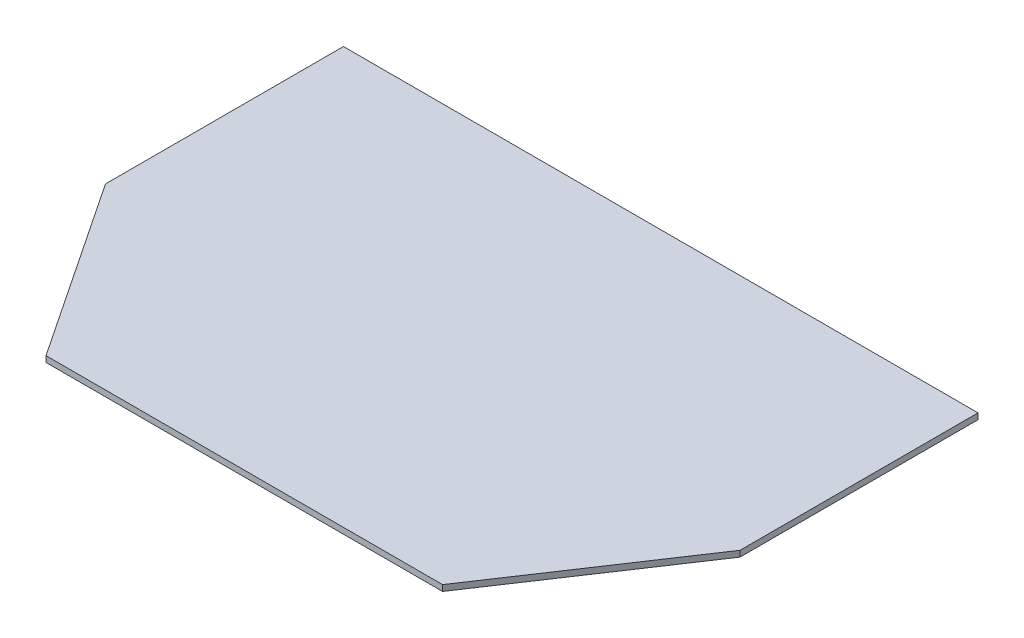
SolidWorks part; units mm, degrees
ref_plane "Front Plane" through (0, 0, 0) normal (0, 0, 1) x (1, 0, 0)
ref_plane "Top Plane" through (0, 0, 0) normal (0, 1, 0) x (1, 0, 0)
ref_plane "Right Plane" through (0, 0, 0) normal (1, 0, 0) x (0, 0, -1)
sketch "Sketch1" plane through (0, 0, 0) normal (0, 1, 0) x (1, 0, 0)
  line L0 (160, 60) -> (-160, 60)
  line L1 (-160, 60) -> (-160, -60)
  line L2 (-160, -60) -> (-100, -150)
  line L3 (-100, -150) -> (100, -150)
  line L4 (100, -150) -> (160, -60)
  line L5 (160, -60) -> (160, 60)
  point P5 (-160, 0)
  point P7 (0, 0)
  dimension "D1" = 320
  dimension "D2" = 120
  dimension "D3" = 120
  dimension "D4" = 90
  dimension "D5" = 200
  dimension "D6" = 60
  dimension "D7" = 150
  dimension "D8" = 160
extrude "Boss-Extrude1" add sketch "Sketch1" along normal blind 3
